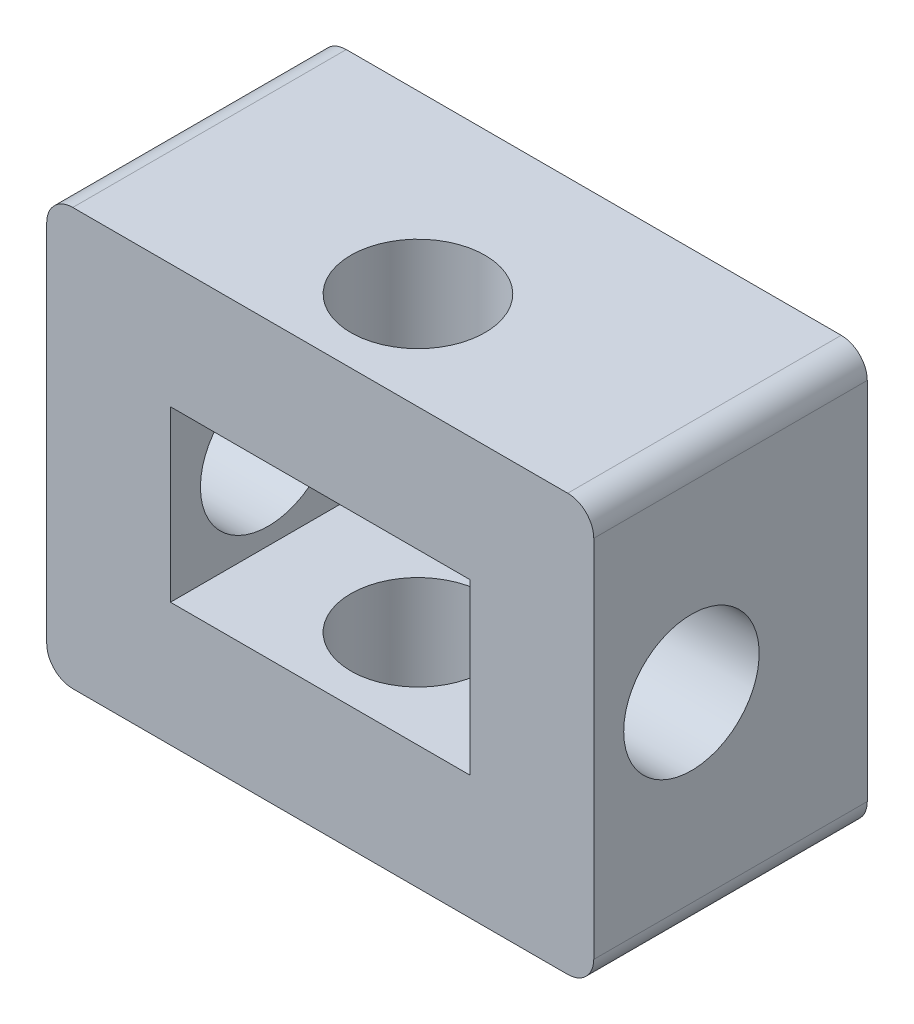
SolidWorks part; units mm, degrees
ref_plane "Front Plane" through (0, 0, 0) normal (0, 0, 1) x (1, 0, 0)
ref_plane "Top Plane" through (0, 0, 0) normal (0, 1, 0) x (1, 0, 0)
ref_plane "Right Plane" through (0, 0, 0) normal (1, 0, 0) x (0, 0, -1)
sketch "Sketch1" plane through (0, 0, 0) normal (0, 0, 1) x (1, 0, 0)
  line L1 (21, -16) -> (-21, -16)
  line L2 (21, -16) -> (21, 16)
  line L3 (21, 16) -> (-21, 16)
  line L4 (-21, -16) -> (-21, 16)
  line L5 (21, -16) -> (-21, 16) construction
  line L6 (21, 16) -> (-21, -16) construction
  point P0 (0, 0)
  dimension "D1" = 42
  dimension "D2" = 32
extrude "Boss-Extrude1" add sketch "Sketch1" along normal blind 21
sketch "Sketch2" plane through (0, 0, 21) normal (0, 0, 1) x (1, 0, 0)
  line L1 (11.5, -6.5) -> (-11.5, -6.5)
  line L2 (11.5, -6.5) -> (11.5, 6.5)
  line L3 (11.5, 6.5) -> (-11.5, 6.5)
  line L4 (-11.5, -6.5) -> (-11.5, 6.5)
  line L5 (11.5, -6.5) -> (-11.5, 6.5) construction
  line L6 (11.5, 6.5) -> (-11.5, -6.5) construction
  point P0 (0, 0)
  dimension "D1" = 23
  dimension "D2" = 13
extrude "Cut-Extrude1" cut sketch "Sketch2" against normal blind 15
sketch "Sketch3" plane through (0, 0, 6) normal (0, 0, 1) x (1, 0, 0)
  circle A0 centre (5.5109, 0.6605) radius 4.5
  dimension "D1" = 9
extrude "Cut-Extrude2" cut sketch "Sketch3" against normal through all
sketch "Sketch4" plane through (11.5, 0, 0) normal (-1, 0, 0) x (0, 0, 1)
  circle A0 centre (13.5, 0) radius 5.2
  dimension "D1" = 10.4
extrude "Cut-Extrude3" cut sketch "Sketch4" against normal through all both and the other way through all
sketch "Sketch5" plane through (0, -6.5, 0) normal (0, 1, 0) x (1, 0, 0)
  circle A0 centre (0, -13.5) radius 5.15
  dimension "D1" = 10.3
extrude "Cut-Extrude4" cut sketch "Sketch5" against normal through all both and the other way through all
fillet "Fillet1" radius 2 4 edges at (21, 16, 10.5) (21, -16, 10.5) (-21, -16, 10.5) (-21, 16, 10.5)
